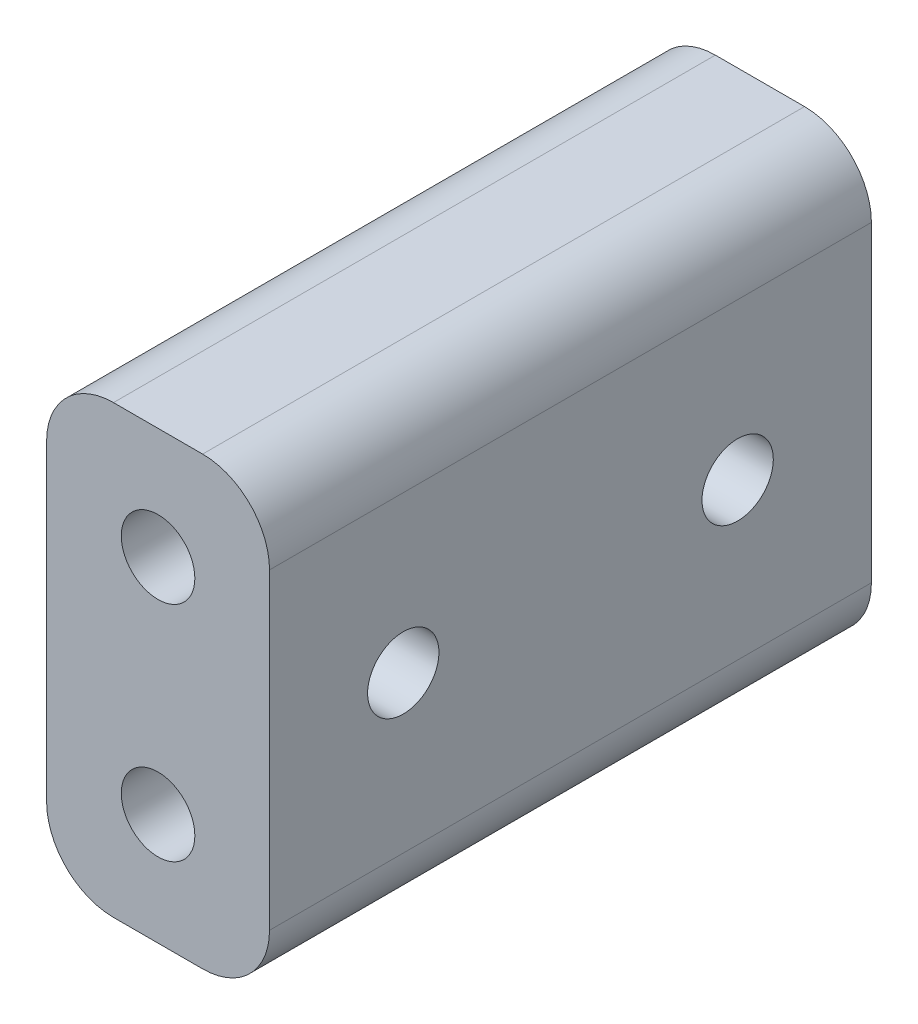
SolidWorks part; units mm, degrees
material "ABS"
ref_plane "前视基准面" through (0, 0, 0) normal (0, 0, 1) x (1, 0, 0)
ref_plane "上视基准面" through (0, 0, 0) normal (0, 1, 0) x (1, 0, 0)
ref_plane "右视基准面" through (0, 0, 0) normal (1, 0, 0) x (0, 0, -1)
other "Configuration Table"
sketch "草图1" plane through (0, 0, 0) normal (0, 0, 1) x (1, 0, 0)
  line L0 (5, 0) -> (5, -20) construction
  line L1 (0, 0) -> (10, 0)
  line L2 (0, 0) -> (0, -20)
  line L3 (0, -20) -> (10, -20)
  line L4 (10, 0) -> (10, -20)
  circle A0 centre (5, -5) radius 1.65
  circle A1 centre (5, -15) radius 1.65
  dimension "D4" = 5
  dimension "D5" = 3.3
  dimension "D1" = 10
  dimension "D2" = 20
  dimension "D3" = 5
extrude "凸台-拉伸1" add sketch "草图1" along normal blind 27
fillet "圆角1" radius 3 4 edges at (0, 0, 13.5) (10, -20, 13.5) (0, -20, 13.5) (10, 0, 13.5)
sketch "草图2" plane through (10, 0, 0) normal (1, 0, 0) x (0, 0, -1)
  line L0 (-27, -10) -> (0, -10) construction
  line L1 (-27, -17) -> (-27, -3) construction
  line L2 (0, -17) -> (0, -3) construction
  line L3 (-21, -10) -> (-6, -10) construction
  line L4 (-13.5, -10) -> (-13.5, -17) construction
  line L5 (-27, -17) -> (0, -17) construction
  circle A0 centre (-21, -10) radius 1.6
  circle A1 centre (-6, -10) radius 1.6
  dimension "D1" = 3.2
  dimension "D2" = 15
extrude "切除-拉伸1" cut sketch "草图2" against normal through all
